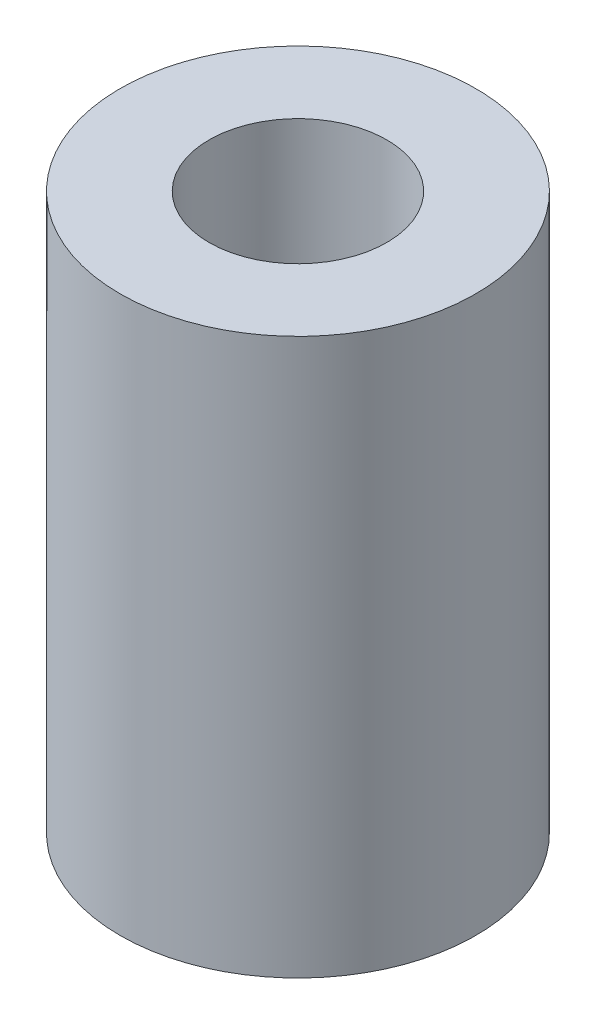
SolidWorks part; units mm, degrees
ref_plane "前视" through (0, 0, 0) normal (0, 0, 1) x (1, 0, 0)
ref_plane "上视" through (0, 0, 0) normal (0, 1, 0) x (1, 0, 0)
ref_plane "右视" through (0, 0, 0) normal (1, 0, 0) x (0, 0, -1)
sketch "草图1" plane through (0, 0, 0) normal (0, 1, 0) x (1, 0, 0)
  circle A0 centre (0, 0) radius 8
  dimension "D1" = 16
extrude "凸台-拉伸1" add sketch "草图1" along normal blind 25
sketch "草图2" plane through (0, 25, 0) normal (0, 1, 0) x (1, 0, 0)
  circle A0 centre (0, 0) radius 4
  dimension "D1" = 8
extrude "切除-拉伸1" cut sketch "草图2" against normal blind 15
sketch "草图3" plane through (0, 0, 0) normal (0, -1, 0) x (1, 0, 0)
  circle A0 centre (0, 0) radius 2.5
  dimension "D1" = 5
extrude "切除-拉伸2" cut sketch "草图3" against normal blind 3
